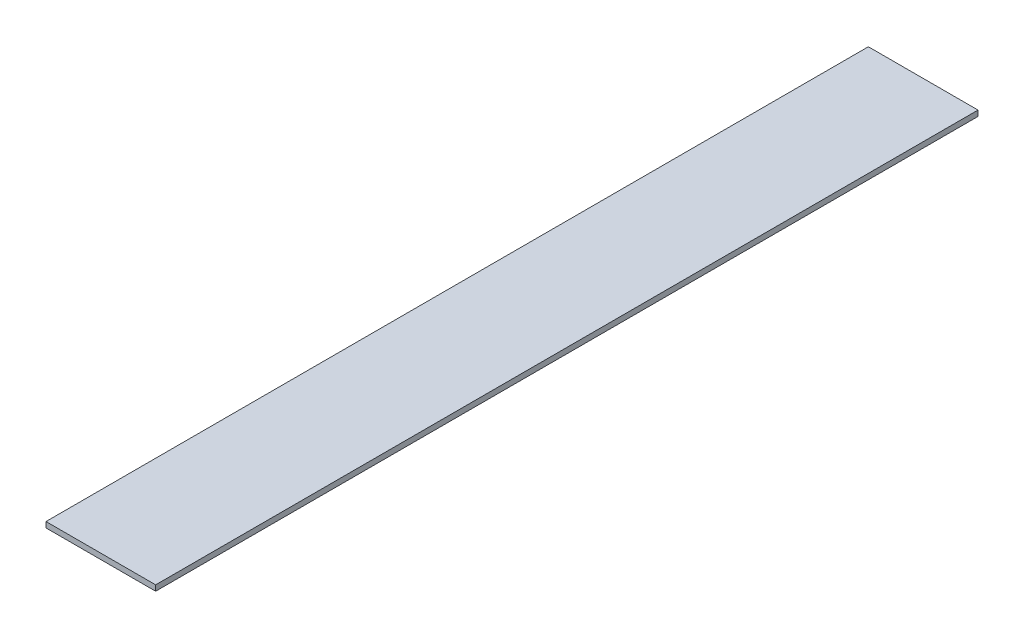
SolidWorks part; units mm, degrees
material "Oak"
ref_plane "Front Plane" through (0, 0, 0) normal (0, 0, 1) x (1, 0, 0)
ref_plane "Top Plane" through (0, 0, 0) normal (0, 1, 0) x (1, 0, 0)
ref_plane "Right Plane" through (0, 0, 0) normal (1, 0, 0) x (0, 0, -1)
sketch "Sketch1" plane through (0, 0, 0) normal (0, 1, 0) x (1, 0, 0)
  line L0 (0, -1000) -> (0, 49000) construction
  line L1 (-1000, -1000) -> (1000, -1000)
  line L2 (-1000, -1000) -> (-1000, 14000)
  line L3 (-1000, 14000) -> (1000, 14000)
  line L4 (1000, -1000) -> (1000, 14000)
  dimension "D1" = 15000
  dimension "D2" = 2000
  dimension "D3" = 1000
extrude "Boss-Extrude1" add sketch "Sketch1" against normal blind 101.6
